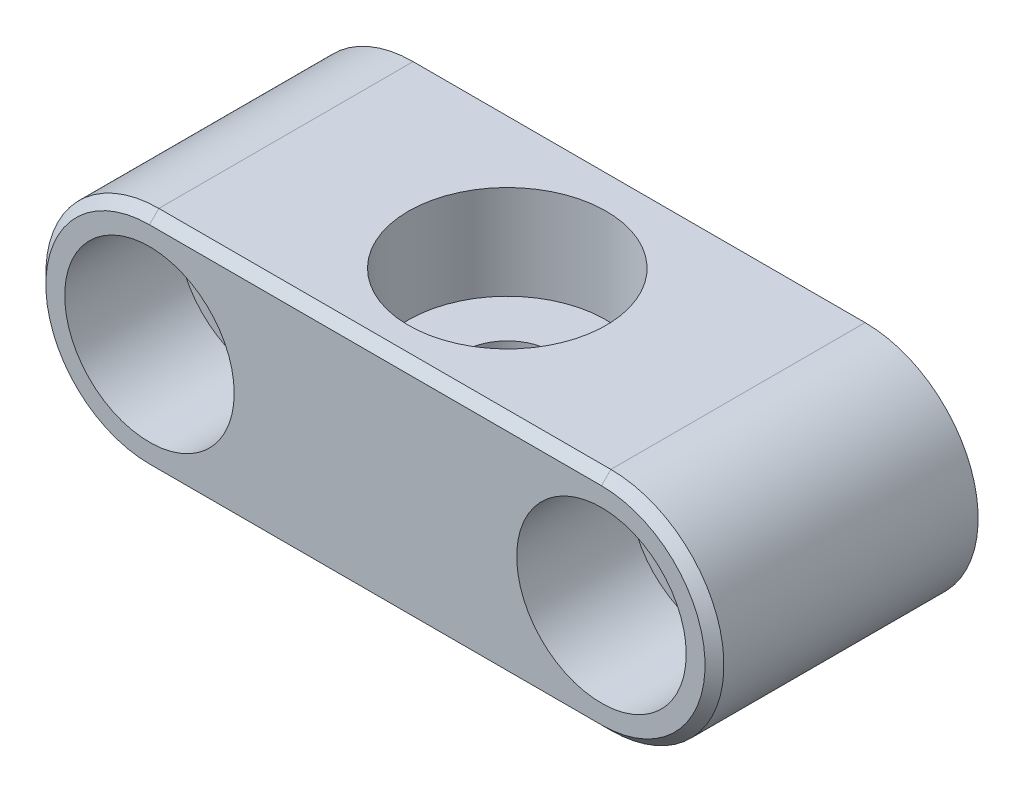
SolidWorks part; units mm, degrees
ref_plane "Front Plane" through (0, 0, 0) normal (0, 0, 1) x (1, 0, 0)
ref_plane "Top Plane" through (0, 0, 0) normal (0, 1, 0) x (1, 0, 0)
ref_plane "Right Plane" through (0, 0, 0) normal (1, 0, 0) x (0, 0, -1)
sketch "Sketch1" plane through (0, 0, 0) normal (0, 0, 1) x (1, 0, 0)
  line L0 (12, 0) -> (-12, 0) construction
  line L1 (12, -6) -> (-12, -6)
  line L2 (12, 6) -> (-12, 6)
  arc A0 (12, -6) -> (12, 6) centre (12, 0) ccw
  arc A1 (-12, 6) -> (-12, -6) centre (-12, 0) ccw
  circle A2 centre (-12, 0) radius 2.75
  circle A3 centre (12, 0) radius 2.75
  point P2 (0, 0)
  dimension "D1" = 24
  dimension "D2" = 6
  dimension "D3" = 5.5
extrude "Boss-Extrude1" add sketch "Sketch1" along normal mid plane 14
sketch "Sketch2" plane through (0, 6, 0) normal (0, 1, 0) x (1, 0, 0)
  circle A0 centre (0, 0) radius 2.35
  dimension "D1" = 4.7
extrude "Cut-Extrude1" cut sketch "Sketch2" against normal through all
sketch "Sketch3" plane through (0, 6, 0) normal (0, 1, 0) x (1, 0, 0)
  circle A0 centre (0, 0) radius 5.25
  dimension "D1" = 10.5
extrude "Cut-Extrude2" cut sketch "Sketch3" against normal blind 5
chamfer "Chamfer1" distance 0.5 angle 45 4 edges at (0, -6, 7) (18, 0, 7) (-18, 0, 7) (0, 6, 7)
sketch "Sketch4" plane through (0, 0, 7) normal (0, 0, 1) x (1, 0, 0)
  circle A0 centre (-12, 0) radius 4.5
  circle A1 centre (12, 0) radius 4.5
  dimension "D1" = 9
extrude "Cut-Extrude3" cut sketch "Sketch4" against normal blind 6
